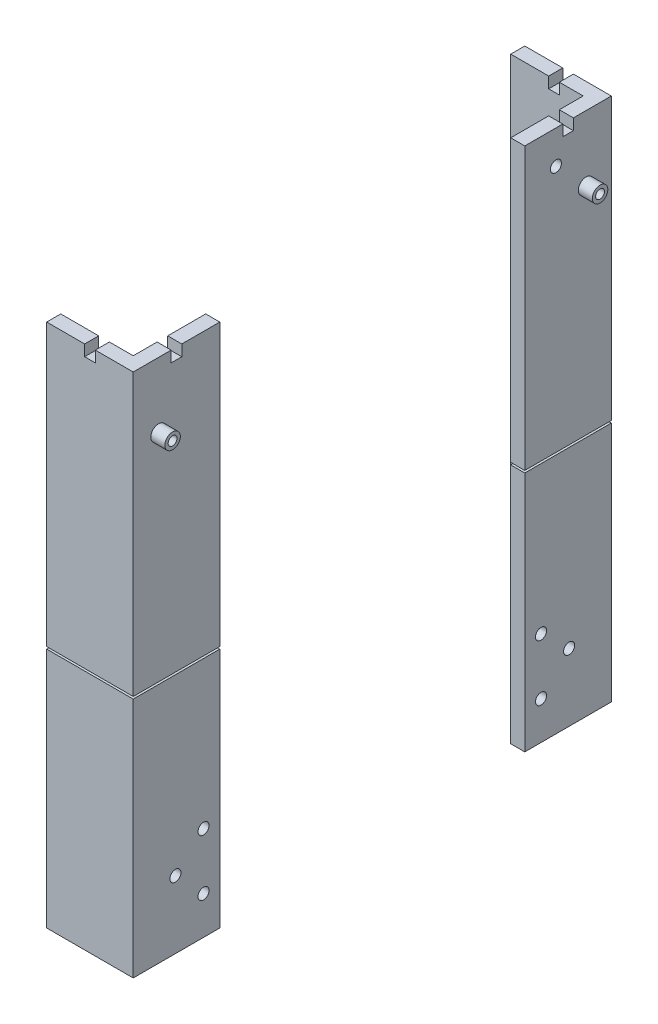
SolidWorks part; units mm, degrees
ref_plane "Front Plane" through (0, 0, 0) normal (0, 0, 1) x (1, 0, 0)
ref_plane "Top Plane" through (0, 0, 0) normal (0, 1, 0) x (1, 0, 0)
ref_plane "Right Plane" through (0, 0, 0) normal (1, 0, 0) x (0, 0, -1)
sketch "Sketch1" plane through (0, 0, 0) normal (0, 0, 1) x (1, 0, 0)
  line L1 (0, 0) -> (-32.7309, 0)
  line L2 (0, 0) -> (0, 237)
  line L3 (0, 237) -> (-32.7309, 237)
  line L4 (-32.7309, 0) -> (-32.7309, 237)
extrude "Boss-Extrude1" add sketch "Sketch1" along normal blind 6.35
sketch "Sketch2" plane through (0, 0, 0) normal (1, 0, 0) x (0, 0, -1)
  line L1 (-6.35, 0) -> (32.73, 0)
  line L2 (-6.35, 0) -> (-6.35, 237)
  line L3 (-6.35, 237) -> (32.73, 237)
  line L4 (32.73, 0) -> (32.73, 237)
  dimension "D1" = 39.08
  dimension "D2" = 237
extrude "Boss-Extrude3" add sketch "Sketch2" along normal blind 6.35
ref_plane "RearMirrorPlane" through (0, 0, -101.6) normal (0, 0, -1) x (-1, 0, 0)
sketch "Sketch27" plane through (6.35, 0, 0) normal (1, 0, 0) x (0, 0, -1)
  line L1 (10.7804, 237) -> (15.5804, 237)
  line L2 (10.7804, 237) -> (10.7804, 232)
  line L3 (10.7804, 232) -> (15.5804, 232)
  line L4 (15.5804, 237) -> (15.5804, 232)
  dimension "D1" = 4.8
  dimension "D2" = 5
extrude "Locking_Mechanism_Cut" cut sketch "Sketch27" against normal up to surface (6.35 mm away) up to face at (0, 118.5, -16.365)
sketch "Sketch28" plane through (6.35, 0, 0) normal (1, 0, 0) x (0, 0, -1)
  circle A1 centre (25.4, 42.545) radius 2.5
  circle A3 centre (25.4, 17.145) radius 2.5
  circle A5 centre (12.7, 30.48) radius 2.5
  dimension "D1" = 5
  dimension "D2" = 5
  dimension "D3" = 5
extrude "Bracket Bolt Holes " cut sketch "Sketch28" against normal up to surface (6.35 mm away) up to face at (0, 176.5, -14.7727)
sketch "Sketch29" plane through (6.35, 0, 0) normal (1, 0, 0) x (0, 0, -1)
  line L0 (-6.35, 237) -> (-6.35, 0) construction
  line L1 (-6.35, 110.0869) -> (32.73, 110.0869)
  line L2 (-6.35, 110.0869) -> (-6.35, 109.0869)
  line L3 (-6.35, 109.0869) -> (32.73, 109.0869)
  line L4 (32.73, 110.0869) -> (32.73, 109.0869)
  line L5 (32.73, 0) -> (32.73, 237) construction
  dimension "D1" = 1
extrude "1 mm split" cut sketch "Sketch29" against normal up to surface (39.0809 mm away) up to face at (-32.7309, 118.5, 3.175)
ref_plane "45Degree" through (0, 0, 0) normal (0.7071, 0, -0.7071) x (0, -1, 0)
mirror "LockingMechanismMirror" about plane through (0, 0, 0) normal (0.7071, 0, -0.7071) of "Locking_Mechanism_Cut"
sketch "Sketch32" plane through (6.35, 0, 0) normal (1, 0, 0) x (0, 0, -1)
  circle A0 centre (5.08, 207.536) radius 3.5
  dimension "D1" = 7
extrude "Locking Mount" add sketch "Sketch32" along normal up to surface (6.35 mm away) separate body
sketch "Sketch33" plane through (12.7, 0, 0) normal (1, 0, 0) x (0, 0, -1)
  circle A0 centre (5.08, 207.536) radius 2
  dimension "D1" = 4
extrude "M4 Screw Hole" cut sketch "Sketch33" against normal up to surface (6.35 mm away) up to face at (6.35, 204.0217, -13.1852)
mirror "Mirror2" about plane through (0, 0, -101.6) normal (0, 0, -1) of bodies 223 224 246 227 230
sketch "Sketch35" plane through (0, 0, 0) normal (-1, 0, 0) x (0, 0, 1)
  circle A0 centre (-184.561, 222) radius 2.5
extrude "Cut-Extrude2" cut sketch "Sketch35" against normal up to surface (6.35 mm away) up to face at (6.35, 204.0217, -190.0148)
